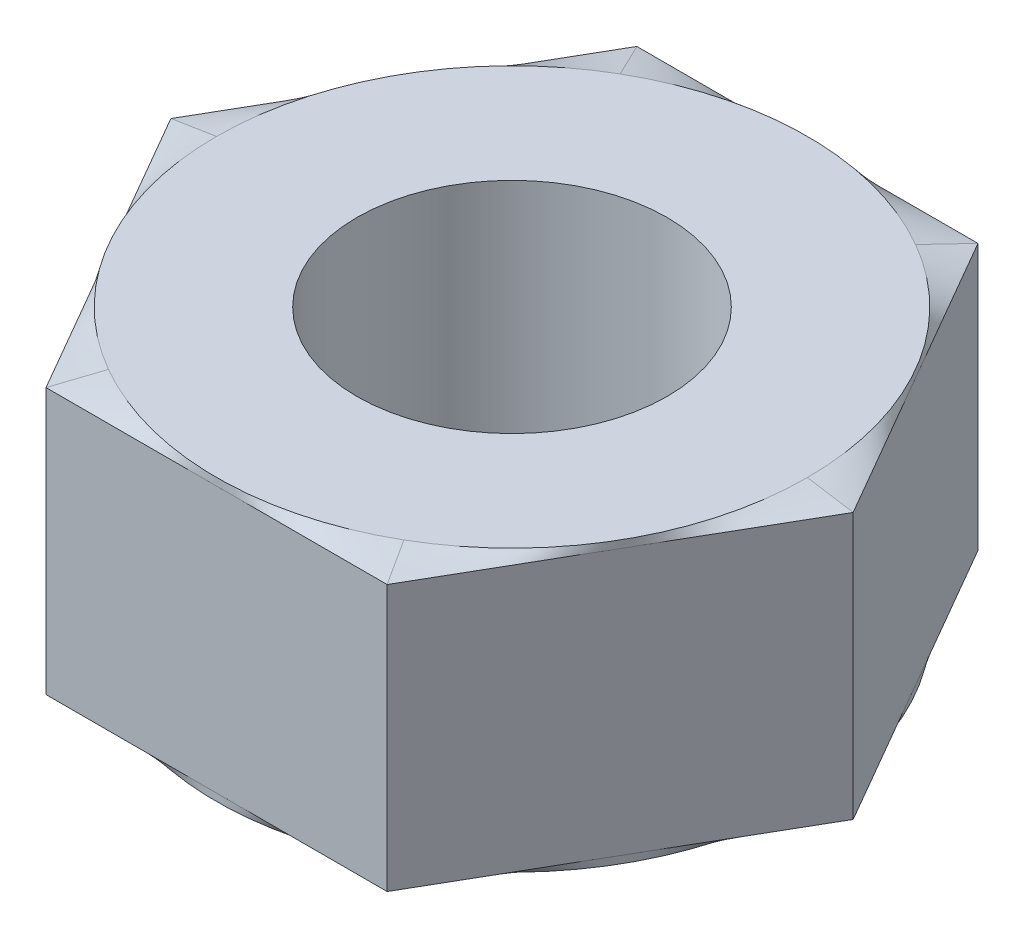
SolidWorks part; units mm, degrees
ref_plane "前视" through (0, 0, 0) normal (0, 0, 1) x (1, 0, 0)
ref_plane "上视" through (0, 0, 0) normal (0, 1, 0) x (1, 0, 0)
ref_plane "右视" through (0, 0, 0) normal (1, 0, 0) x (0, 0, -1)
sketch "草图1" plane through (0, 0, 0) normal (0, 1, 0) x (1, 0, 0)
  line L0 (-4.0854, 0) -> (3.3721, 0) construction
  line L1 (4.6188, 0) -> (2.3094, 4)
  line L2 (2.3094, 4) -> (-2.3094, 4)
  line L3 (-2.3094, 4) -> (-4.6188, 0)
  line L4 (-4.6188, 0) -> (-2.3094, -4)
  line L5 (-2.3094, -4) -> (2.3094, -4)
  line L6 (2.3094, -4) -> (4.6188, 0)
  circle A0 centre (0, 0) radius 4 construction
  dimension "D1" = 8
extrude "凸台-拉伸1" add sketch "草图1" along normal blind 1.8
ref_plane "基准面1" through (0, -0.1, 0) normal (0, -1, 0) x (-1, 0, 0)
sketch "草图3" plane through (0, 0, 0) normal (0, -1, 0) x (1, 0, 0)
  line L6 (4.6188, 0) -> (2.3094, 4)
  line L7 (2.3094, 4) -> (-2.3094, 4)
  line L8 (-2.3094, 4) -> (-4.6188, 0)
  line L9 (-4.6188, 0) -> (-2.3094, -4)
  line L10 (-2.3094, -4) -> (2.3094, -4)
  line L11 (2.3094, -4) -> (4.6188, 0)
  line L12 (4.6188, 0) -> (2.3094, 4)
  line L13 (2.3094, 4) -> (-2.3094, 4)
  line L14 (-2.3094, 4) -> (-4.6188, 0)
  line L15 (-4.6188, 0) -> (-2.3094, -4)
  line L16 (-2.3094, -4) -> (2.3094, -4)
  line L17 (2.3094, -4) -> (4.6188, 0)
  dimension "D1" = 0
sketch "草图4" plane through (0, -0.1, 0) normal (0, -1, 0) x (-1, 0, 0)
  line L0 (4.6188, 0) -> (2.3094, 4) construction
  line L1 (4.6188, 0) -> (2.3094, 4) construction
  circle A0 centre (0, 0) radius 4
loft "放样1" add profiles "草图4", "草图3"
ref_plane "基准面2" through (0, 1.8, 0) normal (0, 1, 0) x (1, 0, 0)
mirror "镜向1" about plane through (0, 1.8, 0) normal (0, 1, 0) of "凸台-拉伸1", "放样1"
sketch "草图5" plane through (0, -0.1, 0) normal (0, 1, 0) x (1, 0, 0)
  circle A0 centre (0, 0) radius 2.1
  dimension "D1" = 4.2
extrude "切除-拉伸1" cut sketch "草图5" along normal through all
cosmetic thread "孔螺蚊线2" parameters "D2"=5
hole_wizard "M5 螺纹孔1" positions "3D草图1" profile "草图6" tap size "M5" standard "ISO" end condition through all
sketch3d "3D草图1"
  line L0 (0, 3.7, 0) -> (0, -0.1, 0) construction
  line L1 (0, 3.7, 0) -> (0, -0.1, 0) construction
  line L2 (0, 3.7, 0) -> (0, -0.1, 0) construction
  point P0 (0, 3.7, 0)
sketch "草图6" plane through (0, 3.7, 0) normal (1, 0, 0) x (0, 0, 1)
  line L0 (0, 0) -> (0, 3.8019)
  line L1 (0, 3.8019) -> (2.1, 3.8019)
  line L2 (2.1, 3.8019) -> (2.1, 0)
  line L5 (2.1, 0) -> (0, 0)
  line L11 (0, -6.35) -> (0, 107.95) construction
  dimension "通孔螺纹孔钻头直径" = 4.2
  dimension "通孔螺纹孔钻头深度" = 3.8019
